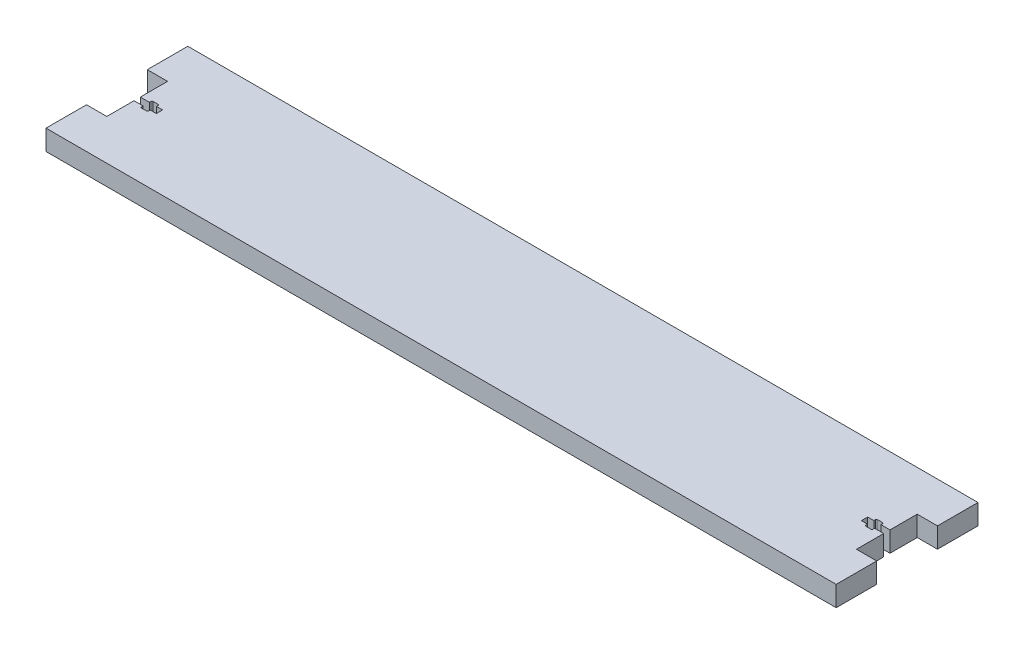
SolidWorks part; units mm, degrees
ref_plane "Front Plane" through (0, 0, 0) normal (0, 0, 1) x (1, 0, 0)
ref_plane "Top Plane" through (0, 0, 0) normal (0, 1, 0) x (1, 0, 0)
ref_plane "Right Plane" through (0, 0, 0) normal (1, 0, 0) x (0, 0, -1)
sketch "Sketch1" plane through (0, 0, 0) normal (0, 1, 0) x (1, 0, 0)
  line L1 (-185, 35) -> (185, 35)
  line L2 (-185, 35) -> (-185, -35)
  line L3 (-185, -35) -> (185, -35)
  line L4 (185, 35) -> (185, -35)
  line L5 (-185, 35) -> (185, -35) construction
  line L6 (-185, -35) -> (185, 35) construction
  point P0 (0, 0)
  dimension "D1" = 370
  dimension "D2" = 70
extrude "Boss-Extrude1" add sketch "Sketch1" along normal blind 10
sketch "Sketch2" plane through (0, 10, 0) normal (0, 1, 0) x (1, 0, 0)
  line L0 (185, 0) -> (204.4903, 0) construction
  line L1 (185, -35) -> (185, 35) construction
  line L2 (185, 35) -> (195, 35)
  line L3 (195, 35) -> (195, 15)
  line L4 (195, 15) -> (185, 15)
  line L5 (185, 15) -> (185, 35)
  line L6 (185, -15) -> (185, -35)
  line L7 (195, -15) -> (185, -15)
  line L8 (195, -35) -> (195, -15)
  line L9 (185, -35) -> (195, -35)
  line L10 (195, 25) -> (185, 25) construction
  line L11 (195, -25) -> (185, -25) construction
  dimension "D1" = 20
  dimension "D2" = 10
extrude "Boss-Extrude2" add sketch "Sketch2" against normal through all
sketch "Sketch3" plane through (0, 10, 0) normal (0, 1, 0) x (1, 0, 0)
  line L0 (185, 0) -> (174, 0) construction
  line L1 (185, -15) -> (185, 15) construction
  line L2 (185, 1.55) -> (174, 1.55) construction
  line L3 (185, -1.55) -> (185, 1.55)
  line L4 (185, 1.55) -> (180.5, 1.55)
  line L5 (180.5, 1.55) -> (180.5, 2.35)
  line L6 (180, 2.85) -> (177.5, 2.85)
  line L7 (177, 2.35) -> (177, 1.55)
  line L8 (177, 1.55) -> (174, 1.55)
  line L9 (174, 1.55) -> (174, -1.55)
  line L10 (185, -1.55) -> (174, -1.55) construction
  line L11 (177, -1.55) -> (174, -1.55)
  line L12 (177, -2.35) -> (177, -1.55)
  line L13 (180, -2.85) -> (177.5, -2.85)
  line L14 (180.5, -1.55) -> (180.5, -2.35)
  line L15 (185, -1.55) -> (180.5, -1.55)
  arc A0 (180.5, 2.35) -> (180, 2.85) centre (180, 2.35) ccw
  arc A1 (177.5, 2.85) -> (177, 2.35) centre (177.5, 2.35) ccw
  arc A2 (177.5, -2.85) -> (177, -2.35) centre (177.5, -2.35) cw
  arc A3 (180.5, -2.35) -> (180, -2.85) centre (180, -2.35) cw
  point P13 (180.5, 2.85)
  point P16 (177, 2.85)
  point P27 (177, -2.85)
  point P28 (180.5, -2.85)
  dimension "D6" = 0.5
  dimension "D1" = 11
  dimension "D2" = 1.55
  dimension "D3" = 3.5
  dimension "D4" = 2.85
  dimension "D5" = 8
extrude "Cut-Extrude1" cut sketch "Sketch3" against normal through all
mirror "Mirror1" about plane through (0, 0, 0) normal (1, 0, 0) of "Cut-Extrude1", "Boss-Extrude2"
equation "\"X-ROD-SPACING\"=45"
equation "\"Y-ROD-SPACING\"=75"
equation "\"Z-ROD-SPACING\"=17.5"
equation "\"Y-BED-OFFSET\"=2"
equation "\"Y-BED-ROD-INSET\"=3.5"
equation "\"Y-BED-SCREW-SPACING\"=209"
equation "\"Y-BED-SCREW-CUTOUT-SLOT-HEIGHT\"=2.5"
equation "\"T-SLOT-NUT-FILLET-RADIUS\"=0.5"
equation "\"T-SLOT-SCREW-SHAFT-RADIUS\"=1.55"
equation "\"T-SLOT-SCREW-SHAFT-CUTOUT-LENGTH\"=11"
equation "\"T-SLOT-NUT-DEPTH\"=3.5"
equation "\"T-SLOT-NUT-WIDTH\"=2.85"
equation "\"T-SLOT-NUT-END-DISTANCE\"=8"
equation "\"ACRYLIC-THICKNESS\"=10"
equation "\"ACRYLIC-THICKNESS2\"=4.5"
equation "\"ACRYLIC-TAB-CUTOUT-SIZE\"=\"ACRYLIC-THICKNESS\"+\"ACRYLIC-TAB-TOLERANCE\"*2"
equation "\"ACRYLIC-TAB-TOLERANCE\"=-.05"
equation "\"KERF\"=0.075"
equation "\"ACRYLIC-THICKNESS-TAB-CUTOUT-WIDTH\"=\"ACRYLIC-THICKNESS\"-\"KERF\"*2"
equation "\"ACRYLIC-THICKNESS-TAB-CUTOUT-HEIGHT\"=\"ACRYLIC-TAB-WIDTH\"-\"KERF\"*4"
equation "\"ACRYLIC-THICKNESS2-TAB-CUTOUT-WIDTH\"=\"ACRYLIC-THICKNESS2\"-\"KERF\"*2"
equation "\"ACRYLIC-THICKNESS2-TAB-CUTOUT-HEIGHT\"=\"ACRYLIC-TAB-WIDTH\"-\"KERF\"*4"
equation "\"ACRYLIC-TAB-WIDTH\"=\"ACRYLIC-THICKNESS\""
equation "\"ACRYLIC-M3-HOLE\"=2.9"
equation "\"SMOOTHROD-CAP-SCREW-DISTANCE\"=20"
equation "\"FRAME-WIDTH-INNER\"=370"
equation "\"NEMA17-HOLE-SPACING\"=31"
equation "\"NEMA17-CENTRAL-CUTOUT\"=22.5"
equation "\"Z-BRACKET-REACH\"=57"
equation "\"Z-ROD-INSET\"=13.5"
equation "\"TOP-BRACKET-SPACING\"=40"
equation "\"SMOOTHROD-X-LENGTH\"=350"
equation "\"SMOOTHROD-Y-LENGTH\"=350"
equation "\"SMOOTHROD-Z-LENGTH\"=350"
equation "\"SMOOTHROD-TIGHTENING-HEADROOM\"=.25"
equation "\"LEADSCREW-Z-LENGTH\"=300"
equation "\"SCREW-LENGTH-FRAME\"=\"ACRYLIC-THICKNESS\" + 10"
equation "\"SCREW-LENGTH-MOTOR\"=\"ACRYLIC-THICKNESS\" + 5"
equation "\"SCREW-LENGTH-EXTRUDER\"=28"
equation "\"SCREW-HEAD-RADIUS\"=6"
equation "\"PRINTED-M3-HOLE\"=3.5"
equation "\"PRINTED-X-SMOOTHROD-DIAMETER\"=8.8"
equation "\"PRINTED-X-SMOOTHROD-CUTOUT\"=10"
equation "\"PRINTED-X-BASE-HEIGHT\"=10"
equation "\"PRINTED-LM8UU-CUTOUT-SIZE\"=15.5"
equation "\"PRINTED-LM8UU-CUTOUT-LENGTH\"=24.5"
equation "\"PRINTED-X-IDLER-HEIGHT\"=16"
equation "\"PRINTED-M3-NUT-AF\"=6.25"
equation "\"PSU-MOUNTING-WIDTH\"=95"
equation "\"PSU-MOUNTING-HEIGHT\"=177"
equation "\"Y-BELT-TO-ROD-DISTANCE\"=20"
equation "\"SPOOL-HOLDER-ROD-SPACING\"=150"
equation "\"ACRYLIC-X-CARRIAGE-WIDTH\"=55"
equation "\"ACRYLIC-X-CARRIAGE-HEIGHT\"=75"
equation "\"ACRYLIC-X-CARRIAGE-LM8UU-CUTOUT-WIDTH\"=24.25"
equation "\"ACRYLIC-X-CARRIAGE-LM8UU-CUTOUT-HEIGHT\"=11.0"
equation "\"ACRYLIC-X-CARRIAGE-SCREW-SPACING-X\"=15"
equation "\"ACRYLIC-X-CARRIAGE-SCREW-SPACING-Y\"=33"
equation "\"ACRYLIC-X-CARRIAGE-CENTER-TAB-SPACING\"=14"
equation "\"ACRYLIC-X-CARRIAGE-EXTRUDER-OFFSET\"=26"
equation "\"ACRYLIC-X-CARRIAGE-EXTRUDER-ANGLE\"=90"
equation "\"ACRYLIC-X-CARRIAGE-EXTRUDER-SHELF-DEPTH\"=\"ACRYLIC-X-CARRIAGE-EXTRUDER-OFFSET\" + 28"
equation "\"ACRYLIC-X-CARRIAGE-EXTRUDER-BRACE-SPACING\"=23"
equation "\"ACRYLIC-X-CARRIAGE-EXTRUDER-BRACE-TAB-OFFSET\"=20"
equation "\"ACRYLIC-X-CARRIAGE-EXTRUDER-BRACE-HEIGHT\"=35"
equation "\"ACRYLIC-X-CARRIAGE-EXTRUDER-BRACE-SCREW-SPACING\"=22"
equation "\"ACRYLIC-X-CARRIAGE-DUAL-WIDTH-MULTIPLIER\"=1.65"
equation "\"ACRYLIC-X-CARRIAGE-DUAL-HOTEND-SPACING\"=42"
equation "\"ACRYLIC-X-CARRIAGE-DUAL-WIDTH\"=75"
equation "\"ACRYLIC-X-CARRIAGE-DUAL-FAN-OFFSET\"=52"
equation "\"ACRYLIC-X-CARRIAGE-DUAL-FAN-HEIGHT\"=20"
equation "\"ACRYLIC-X-CARRIAGE-DUAL-HOTEND-SEPARATION\"=36"
equation "\"ACRYLIC-X-CARRIAGE-DUAL-MOUNT-PLATE-DEPTH\"=75"
equation "\"ACRYLIC-X-CARRIAGE-DUAL-MOUNT-BRACE-WIDTH\"=33"
equation "\"ACRYLIC-X-CARRIAGE-DUAL-MOUNT-SCREW-WIDTH\"=40"
equation "\"BLOWER-FAN-WIDTH\"=15"
equation "\"D1@Sketch1\"=\"FRAME-WIDTH-INNER\""
equation "\"D1@Boss-Extrude1\"=\"ACRYLIC-THICKNESS\""
equation "\"D2@Sketch2\"=\"ACRYLIC-THICKNESS\""
equation "\"D1@Sketch3\"=\"T-SLOT-SCREW-SHAFT-CUTOUT-LENGTH\""
equation "\"D2@Sketch3\"=\"T-SLOT-SCREW-SHAFT-RADIUS\""
equation "\"D3@Sketch3\"=\"T-SLOT-NUT-DEPTH\""
equation "\"D4@Sketch3\"=\"T-SLOT-NUT-WIDTH\""
equation "\"D5@Sketch3\"=\"T-SLOT-NUT-END-DISTANCE\""
equation "\"D6@Sketch3\"=\"T-SLOT-NUT-FILLET-RADIUS\""
